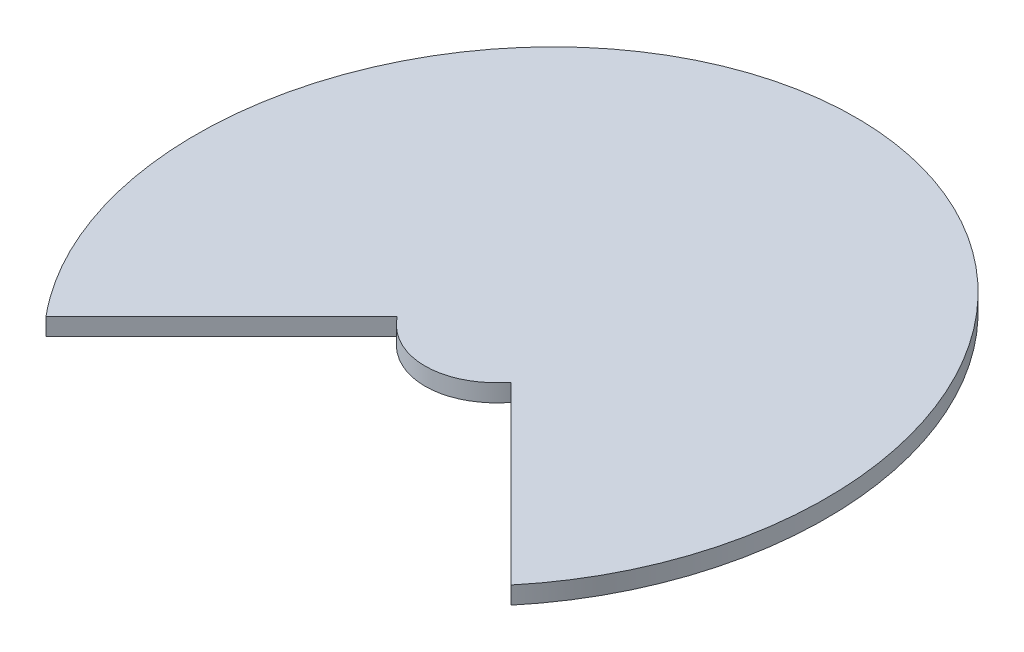
SolidWorks part; units mm, degrees
ref_plane "Front Plane" through (0, 0, 0) normal (0, 0, 1) x (1, 0, 0)
ref_plane "Top Plane" through (0, 0, 0) normal (0, 1, 0) x (1, 0, 0)
ref_plane "Right Plane" through (0, 0, 0) normal (1, 0, 0) x (0, 0, -1)
sketch "Sketch1" plane through (0, 0, 0) normal (0, 1, 0) x (1, 0, 0)
  line L1 (-38.4378, 79.9246) -> (-102.1369, 16.2255)
  line L2 (2.9169, 79.9246) -> (66.6159, 16.2255)
  ellipse E0 centre (-17.7605, 100.6019) end of major axis (-17.7605, -24.4779) minor radius 114.3 (66.6159, 16.2255) -> (-102.1369, 16.2255) ccw
  ellipse E1 centre (-17.7605, 100.6019) end of major axis (-17.7605, 69.3987) minor radius 27.6098 (-38.4378, 79.9246) -> (2.9169, 79.9246) ccw
extrude "Boss-Extrude1" add sketch "Sketch1" along normal blind 6.35
